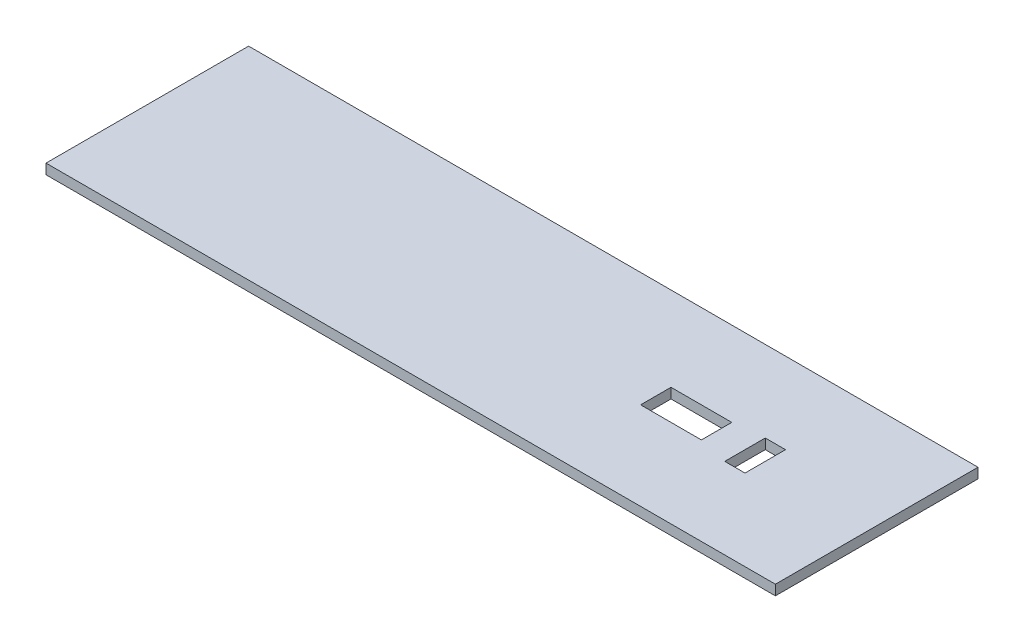
SolidWorks part; units mm, degrees
ref_plane "Alzado" through (0, 0, 0) normal (0, 0, 1) x (1, 0, 0)
ref_plane "Planta" through (0, 0, 0) normal (0, 1, 0) x (1, 0, 0)
ref_plane "Vista lateral" through (0, 0, 0) normal (1, 0, 0) x (0, 0, -1)
sketch "Croquis1" plane through (0, 0, 0) normal (0, 1, 0) x (1, 0, 0)
  line L1 (-360, -100) -> (360, -100)
  line L2 (-360, -100) -> (-360, 100)
  line L3 (-360, 100) -> (360, 100)
  line L4 (360, -100) -> (360, 100)
  line L5 (-360, -100) -> (360, 100) construction
  line L6 (-360, 100) -> (360, -100) construction
  point P0 (0, 0)
  dimension "D1" = 720
  dimension "D2" = 200
extrude "Saliente-Extruir1" add sketch "Croquis1" along normal blind 10
sketch "Croquis2" plane through (0, 0, 0) normal (0, -1, 0) x (-1, 0, 0)
  line L0 (-360, 0) -> (-240, 0)
  line L1 (-360, -100) -> (-360, 100) construction
  line L3 (-250, 20) -> (-230, 20)
  line L4 (-250, 20) -> (-250, -20)
  line L5 (-250, -20) -> (-230, -20)
  line L6 (-230, 20) -> (-230, -20)
  line L7 (-250, 20) -> (-230, -20) construction
  line L8 (-250, -20) -> (-230, 20) construction
  dimension "D1" = 120
  dimension "D2" = 20
  dimension "D3" = 40
extrude "Cortar-Extruir1" cut sketch "Croquis2" against normal blind 10 contours L3 L6 L5 L4
sketch "Croquis3" plane through (0, 10, 0) normal (0, 1, 0) x (1, 0, 0)
  line L3 (140.1458, -13.1845) -> (200.1458, -13.1845)
  line L4 (140.1458, -13.1845) -> (140.1458, 16.8155)
  line L5 (140.1458, 16.8155) -> (200.1458, 16.8155)
  line L6 (200.1458, -13.1845) -> (200.1458, 16.8155)
  dimension "D2" = 30
  dimension "D3" = 60
extrude "Cortar-Extruir2" cut sketch "Croquis3" against normal up to surface (10 mm away) up to face at (240, 0, 0)
